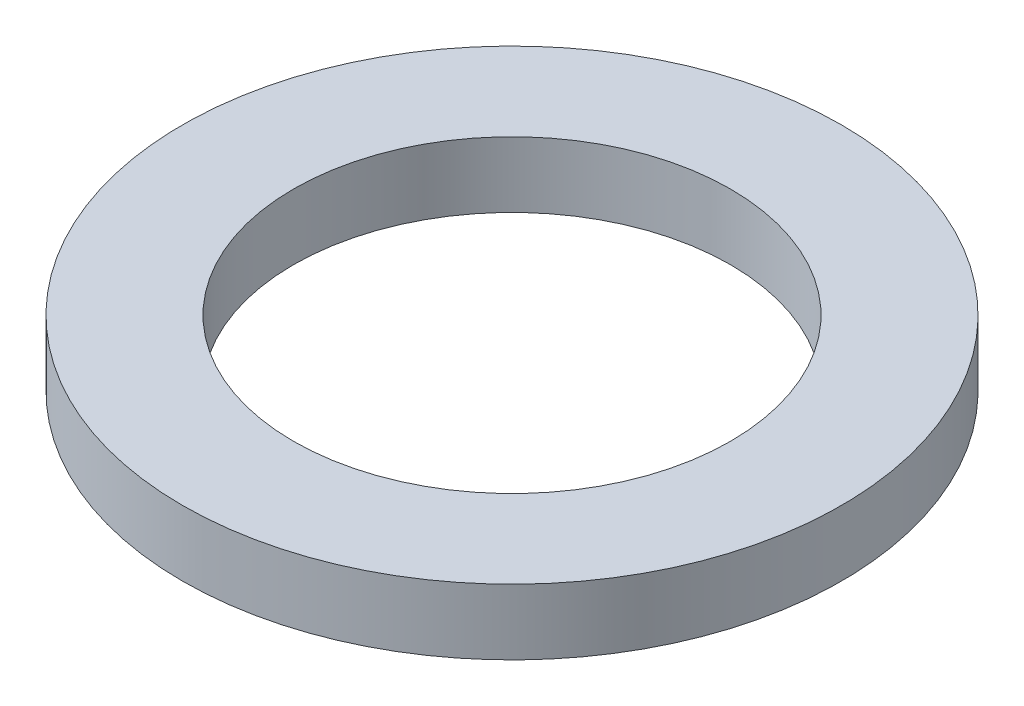
SolidWorks part; units mm, degrees
ref_plane "Front Plane" through (0, 0, 0) normal (0, 0, 1) x (1, 0, 0)
ref_plane "Top Plane" through (0, 0, 0) normal (0, 1, 0) x (1, 0, 0)
ref_plane "Right Plane" through (0, 0, 0) normal (1, 0, 0) x (0, 0, -1)
sketch "Sketch1" plane through (0, 0, 0) normal (0, 1, 0) x (1, 0, 0)
  line L0 (-1.5875, 1.5875) -> (-1.5875, -1.5875) construction
  line L1 (-1.5875, -1.5875) -> (1.5875, -1.5875) construction
  circle A0 centre (0, 0) radius 2.2451 construction
  circle A1 centre (0, 0) radius 3.7691
  circle A2 centre (0, 0) radius 2.4991
  dimension "D1" = 3.175
  dimension "D3" = 1.27
  dimension "D2" = 0.254
extrude "Boss-Extrude1" add sketch "Sketch1" along normal blind 0.75
